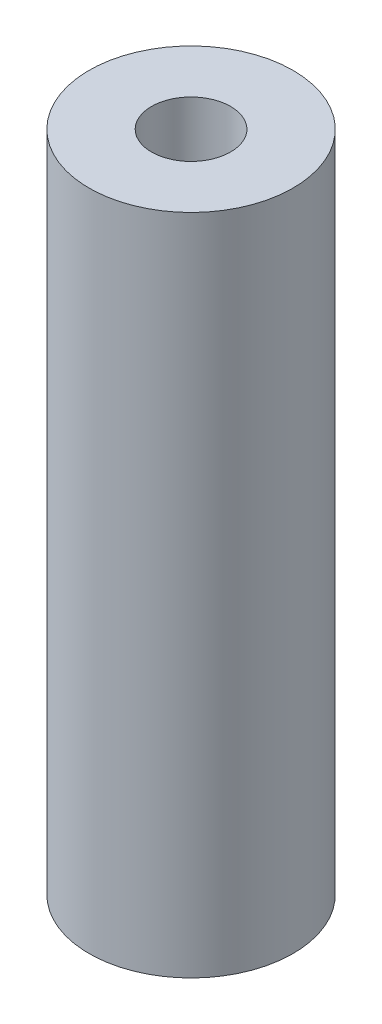
SolidWorks part; units mm, degrees
ref_plane "Front Plane" through (0, 0, 0) normal (0, 0, 1) x (1, 0, 0)
ref_plane "Top Plane" through (0, 0, 0) normal (0, 1, 0) x (1, 0, 0)
ref_plane "Right Plane" through (0, 0, 0) normal (1, 0, 0) x (0, 0, -1)
sketch "Sketch1" plane through (0, 0, 0) normal (0, 1, 0) x (1, 0, 0)
  circle A0 centre (0, 0) radius 1.55
  circle A1 centre (0, 0) radius 4
  dimension "D1" = 3.1
  dimension "D2" = 8
extrude "Boss-Extrude1" add sketch "Sketch1" along normal blind 26
